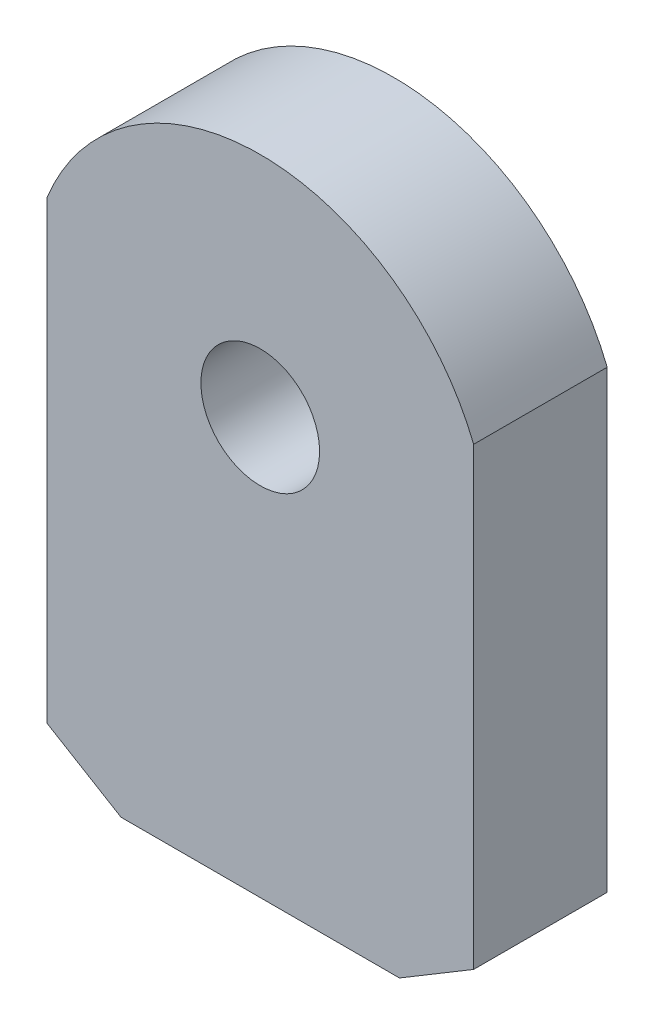
SolidWorks part; units mm, degrees
ref_plane "正面" through (0, 0, 0) normal (0, 0, 1) x (1, 0, 0)
ref_plane "平面" through (0, 0, 0) normal (0, 1, 0) x (1, 0, 0)
ref_plane "右側面" through (0, 0, 0) normal (1, 0, 0) x (0, 0, -1)
sketch "ｽｹｯﾁ1" plane through (0, 0, 0) normal (0, 0, 1) x (1, 0, 0)
  line L0 (0, 0) -> (0, -0.16) construction
  line L1 (23.0125, 0) -> (-23.0125, 0) construction
  line L2 (14.385, -28.04) -> (-14.385, -28.04)
  line L3 (14.385, -28.04) -> (14.385, -5.6125)
  line L5 (-14.385, -28.04) -> (-14.385, -5.6125)
  line L6 (14.385, -28.04) -> (-14.385, 5.6125) construction
  line L7 (14.385, 5.6125) -> (-14.385, -28.04) construction
  line L12 (-14.385, 5.6125) -> (-14.385, -5.6125)
  line L13 (14.385, 5.6125) -> (14.385, -5.6125)
  circle A0 centre (0, 0) radius 4
  arc A6 (14.385, 5.6125) -> (-14.385, 5.6125) centre (0, -0.16) ccw
  point P4 (-26.25, 0)
  point P5 (0, -11.2137)
  point P12 (0, 0)
  point P16 (26.25, 0)
  point P26 (0, 15.34)
  dimension "D1" = 8
  dimension "D2" = 28.77
  dimension "D3" = 15.5
  dimension "D6" = 0.16
  dimension "D4" = 28.77
  dimension "D7" = 43.38
  dimension "D8" = 46.025
extrude "ﾎﾞｽ - 押し出し1" add sketch "ｽｹｯﾁ1" along normal blind 9
chamfer "面取り1" distance 5 distance2 3 1 edges at (14.385, -28.04, 4.5)
chamfer "面取り2" distance 3 distance2 5 1 edges at (-14.385, -28.04, 4.5)
